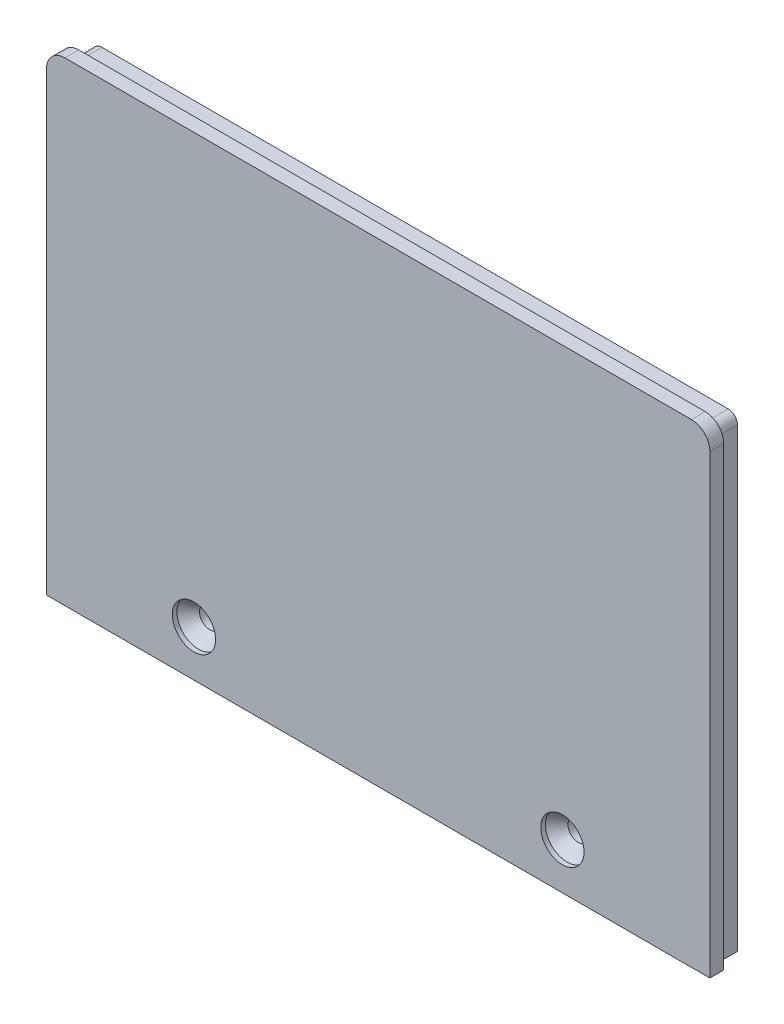
SolidWorks part; units mm, degrees
ref_plane "Front Plane" through (0, 0, 0) normal (0, 0, 1) x (1, 0, 0)
ref_plane "Top Plane" through (0, 0, 0) normal (0, 1, 0) x (1, 0, 0)
ref_plane "Right Plane" through (0, 0, 0) normal (1, 0, 0) x (0, 0, -1)
sketch "Sketch1" plane through (0, 0, 0) normal (0, 0, 1) x (1, 0, 0)
  line L8 (70, 0) -> (70, 99)
  line L9 (68, 101) -> (-68, 101)
  line L10 (-70, 99) -> (-70, 0)
  line L11 (-70, 0) -> (70, 0)
  line L12 (70, 0) -> (70, 99)
  line L13 (68, 101) -> (-68, 101)
  line L14 (-70, 99) -> (-70, 0)
  line L15 (-70, 0) -> (70, 0)
  arc A4 (70, 99) -> (68, 101) centre (68, 99) ccw
  arc A5 (-68, 101) -> (-70, 99) centre (-68, 99) ccw
  arc A6 (70, 99) -> (68, 101) centre (68, 99) ccw
  arc A7 (-68, 101) -> (-70, 99) centre (-68, 99) ccw
  dimension "D1" = 0
extrude "Boss-Extrude1" add sketch "Sketch1" along normal blind 8
sketch "Sketch2" plane through (0, 0, 8) normal (0, 0, 1) x (1, 0, 0)
  line L4 (72, 0) -> (72, 99)
  line L5 (-72, 0) -> (72, 0)
  line L6 (-72, 99) -> (-72, 0)
  line L7 (68, 103) -> (-68, 103)
  line L8 (72, 0) -> (72, 99)
  line L9 (-72, 0) -> (72, 0)
  line L10 (-72, 99) -> (-72, 0)
  line L11 (68, 103) -> (-68, 103)
  arc A2 (-68, 103) -> (-72, 99) centre (-68, 99) ccw
  arc A3 (72, 99) -> (68, 103) centre (68, 99) ccw
  arc A4 (-68, 103) -> (-72, 99) centre (-68, 99) ccw
  arc A5 (72, 99) -> (68, 103) centre (68, 99) ccw
  dimension "D1" = 0
extrude "Boss-Extrude2" add sketch "Sketch2" against normal blind 3
hole_wizard "CSK for M4 Countersunk Flat Head Screw1" positions "Sketch4" profile "Sketch3" countersink size "M4" standard "ISO" end condition through all
sketch "Sketch4" plane through (0, 0, 8) normal (0, 0, 1) x (1, 0, 0)
  point P2 (40, 10)
sketch "Sketch3" plane through (40, 10, 8) normal (1, 0, 0) x (0, -1, 0)
  line L0 (0, 0) -> (0, 8)
  line L1 (0, 8) -> (2.25, 8)
  line L2 (2.25, 8) -> (2.25, 3.45)
  line L3 (2.25, 3.45) -> (4.7, 1)
  line L4 (4.7, 1) -> (4.7, 0)
  line L6 (4.7, 0) -> (0, 0)
  line L7 (-2.25, 3.45) -> (-4.7, 1) construction
  line L11 (0, -6.35) -> (0, 107.95) construction
  dimension "Thru Hole Dia." = 4.5
  dimension "Thru Hole Depth" = 8
  dimension "C'Sink Dia." = 9.4
  dimension "C'Sink Angle" = 90
  dimension "Head Clearance" = 1
mirror "Mirror1" about plane through (0, 0, 0) normal (1, 0, 0) of "CSK for M4 Countersunk Flat Head Screw1"
